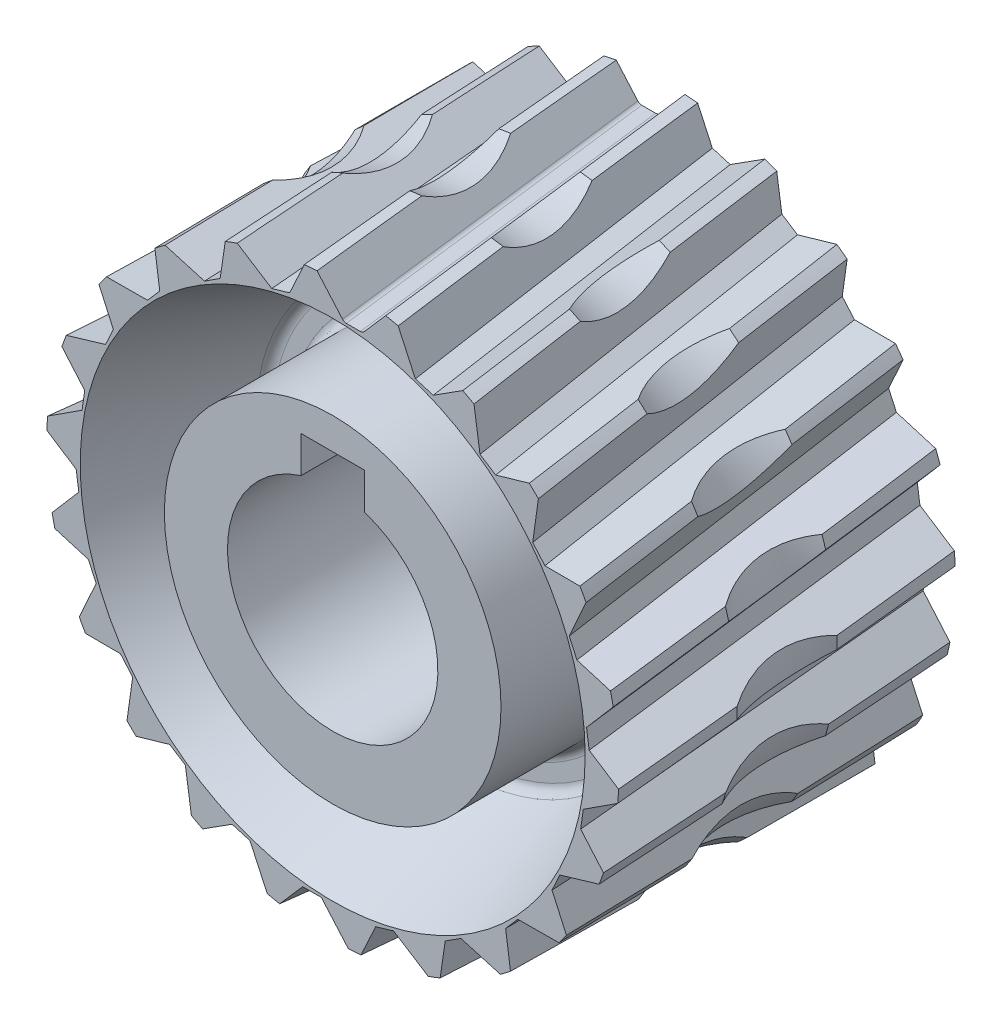
SolidWorks part; units mm, degrees
ref_plane "Front Plane" through (0, 0, 0) normal (0, 0, 1) x (1, 0, 0)
ref_plane "Top Plane" through (0, 0, 0) normal (0, 1, 0) x (1, 0, 0)
ref_plane "Right Plane" through (0, 0, 0) normal (1, 0, 0) x (0, 0, -1)
sketch "Sketch2" plane through (0, 0, 0) normal (0, 0, 1) x (1, 0, 0)
  circle A0 centre (0, 0) radius 28.575
  circle A1 centre (0, 0) radius 7.9375
  dimension "D1" = 57.15
  dimension "D2" = 15.875
extrude "Boss-Extrude1" add sketch "Sketch2" along normal mid plane 25.4
sketch "Sketch3" plane through (0, 0, 0) normal (1, 0, 0) x (0, 0, -1)
  line L0 (12.7, 28.575) -> (-12.7, 28.575) construction
  circle A0 centre (0, 28.575) radius 7.9375
  dimension "D1" = 15.875
revolve "Cut-Revolve1" cut sketch "Sketch3" angle 360 about axis through (0, 0, 12.7) along (0, 0, -1)
sketch "Sketch4" plane through (0, 0, 0) normal (1, 0, 0) x (0, 0, -1)
  line L0 (12.7, 12.7) -> (2.54, 12.7)
  line L2 (12.7, -28.575) -> (12.7, 28.575) construction
  line L3 (2.54, 12.7) -> (2.54, 15.24)
  line L4 (2.54, 15.24) -> (12.7, 19.05)
  line L5 (12.7, 19.05) -> (12.7, 12.7)
  line L19 (1.1693, 0) -> (18.7167, 0) construction
  dimension "D1" = 2.54
  dimension "D2" = 10.16
  dimension "D3" = 38.1
  dimension "D4" = 25.4
revolve "Cut-Revolve2" cut sketch "Sketch4" angle 360 about L19
mirror "Mirror1" about plane through (0, 0, 0) normal (0, 0, 1) of "Cut-Revolve2"
chamfer "Chamfer2" distance 2.54 angle 45 2 edges at (28.575, 0, -12.7) (28.575, 0, 12.7)
fillet "Fillet1" radius 0.7874 4 edges at (15.24, 0, -2.54) (12.7, 0, -2.54) (12.7, 0, 2.54) (15.24, 0, 2.54)
sketch "Sketch5" plane through (0, 0, 0) normal (0, 0, 1) x (1, 0, 0)
  line L2 (2.3876, 0) -> (-2.3876, 0)
  line L3 (2.3876, 0) -> (2.3876, 10.3251)
  line L4 (2.3876, 10.3251) -> (-2.3876, 10.3251)
  line L5 (-2.3876, 0) -> (-2.3876, 10.3251)
  circle A4 centre (0, 0) radius 7.9375 construction
  dimension "D1" = 4.7752
  dimension "D2" = 2.3876
extrude "Cut-Extrude1" cut sketch "Sketch5" against normal through all both and the other way through all
ref_plane "Plane1" through (0, 24.13, 0) normal (0, 1, 0) x (1, 0, 0)
sketch "Sketch6" plane through (0, 24.13, 0) normal (0, 1, 0) x (1, 0, 0)
  line L0 (1.9492, -15.875) -> (-2.5239, 20.5557)
  line L1 (0, 0) -> (0, 21.6672) construction
  line L3 (-26.035, -12.7) -> (26.035, -12.7) construction
  dimension "D1" = 7
  dimension "D2" = 3.175
ref_plane "Plane2" through (1.9492, 24.13, 15.875) normal (-0.1219, 0, -0.9925) x (-0.9925, 0, 0.1219)
sketch "Sketch8" plane through (0, 0, 0) normal (1, 0, 0) x (0, 0, -1)
  line L0 (0, 0) -> (-20.1146, 0) construction
  line L1 (-12.7, 21.59) -> (12.7, 21.59)
  line L2 (-12.7, 26.035) -> (-12.7, -26.035) construction
  line L3 (12.7, -26.035) -> (12.7, 26.035) construction
  line L4 (12.7, 21.59) -> (12.7, 29.0384)
  line L5 (-12.7, 21.59) -> (-12.7, 29.0384)
  line L7 (-12.7, 29.0384) -> (12.7, 29.0384)
  dimension "D1" = 43.18
revolve "Cut-Revolve3" cut sketch "Sketch8" angle 360 about L0
sketch "Sketch10" plane through (1.9492, 24.13, 15.875) normal (-0.1219, 0, -0.9925) x (-0.9925, 0, 0.1219)
  line L0 (10.1185, 5.967) -> (0.6985, -4.9022)
  line L1 (0.6985, -4.9022) -> (-0.6985, -4.9022)
  line L2 (-0.6985, -4.9022) -> (-10.1185, 5.967)
  line L3 (-10.1185, 5.967) -> (10.1185, 5.967)
  line L4 (0, -4.9022) -> (0, 0) construction
  line L5 (-2.3495, -2.9972) -> (2.3495, -2.9972) construction
  point P12 (0, -2.9972)
  dimension "D1" = 1.397
  dimension "D2" = 4.699
  dimension "D3" = 1.905
  dimension "D4" = 2.9972
sweep "Cut-Sweep1" cut profiles "Sketch10" path "Sketch6"
fillet "Fillet2" radius 0.381 2 edges at (0.7037, 19.2278, 0) (-0.7037, 19.2278, 0)
pattern_circular "CirPattern1" count 22 over 360 about axis through (0, 0, 0) along (0, 0, 1) of "Cut-Sweep1"
